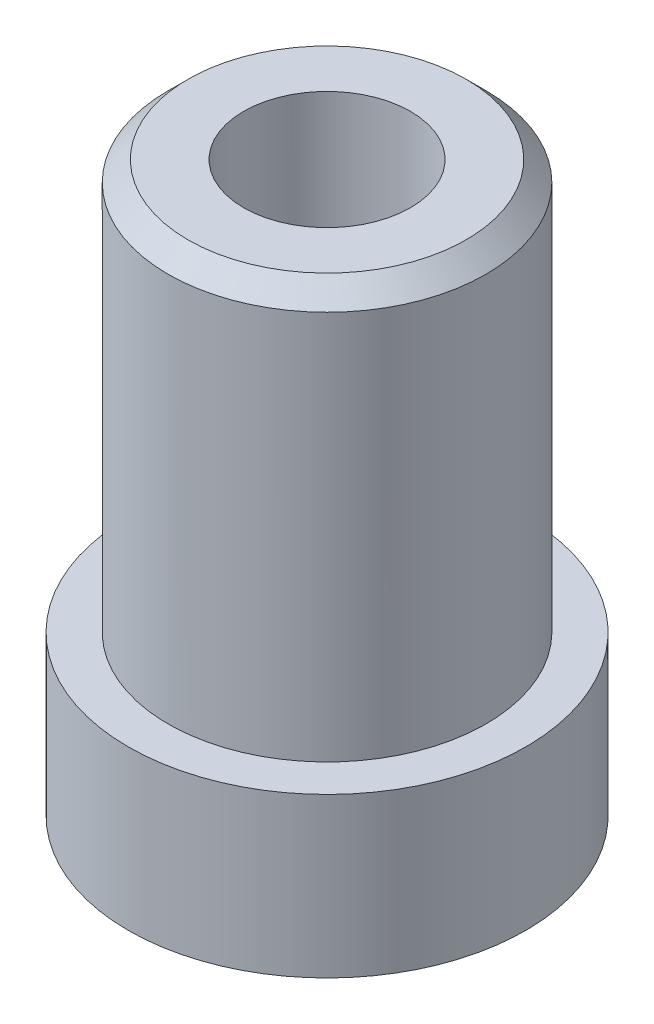
SolidWorks part; units mm, degrees
ref_plane "前视基准面" through (0, 0, 0) normal (0, 0, 1) x (1, 0, 0)
ref_plane "上视基准面" through (0, 0, 0) normal (0, 1, 0) x (1, 0, 0)
ref_plane "右视基准面" through (0, 0, 0) normal (1, 0, 0) x (0, 0, -1)
sketch "草图1" plane through (0, 0, 0) normal (0, 1, 0) x (1, 0, 0)
  circle A0 centre (0, 0) radius 4
  dimension "D1" = 8
extrude "凸台-拉伸1" add sketch "草图1" along normal mid plane 14.3
sketch "草图2" plane through (0, 0, 0) normal (0, 0, 1) x (1, 0, 0)
  line L0 (4, -7.15) -> (5, -7.15)
  line L1 (5, -7.15) -> (5, -3.15)
  line L2 (5, -3.15) -> (4, -3.15)
  line L3 (4, -3.15) -> (4, -7.15)
  dimension "D1" = 1
  dimension "D2" = 4
revolve "旋转1" add sketch "草图2" angle 360 about axis through (0, 7.15, 0) along (0, -1, 0)
chamfer "倒角1" distance 0.5 angle 45 1 edges at (0, 7.15, 4)
hole_wizard "M5 螺纹孔1" positions "草图5" profile "草图4" tap size "M5" standard "GB"
sketch "草图5" plane through (0, -7.15, 0) normal (0, -1, 0) x (-1, 0, 0)
  point P0 (0, 0)
sketch "草图4" plane through (0, -7.15, 0) normal (1, 0, 0) x (0, 0, -1)
  line L0 (0, 0) -> (0, 18.6618)
  line L1 (0, 18.6618) -> (2.1, 17.4)
  line L2 (2.1, 17.4) -> (2.1, 0)
  line L5 (2.1, 0) -> (0, 0)
  line L10 (0, 18.6618) -> (-2.1, 17.4) construction
  line L11 (0, -6.35) -> (0, 107.95) construction
  dimension "螺纹孔钻头直径" = 4.2
  dimension "螺纹孔钻头深度" = 17.4
  dimension "导头角度" = 118
cosmetic thread "孔螺蚊线1" parameters "D1"=14.3, "D2"=5
